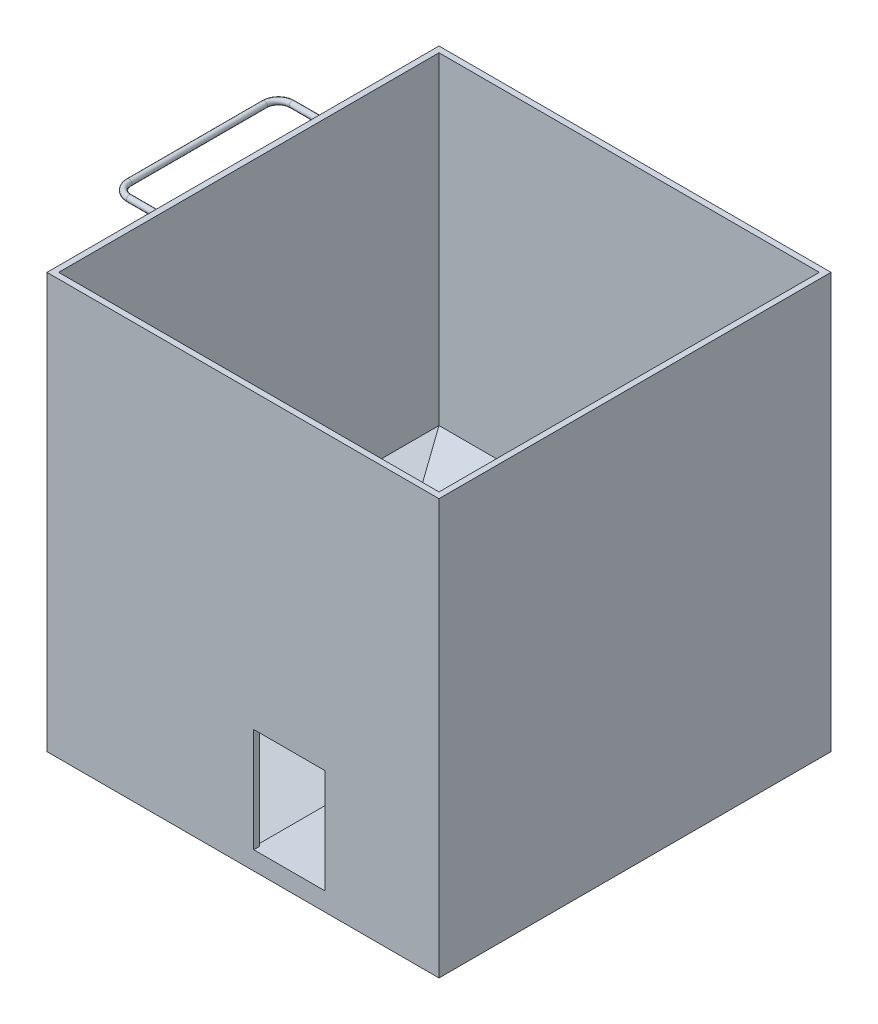
SolidWorks part; units mm, degrees
ref_plane "Front" through (0, 0, 0) normal (0, 0, 1) x (1, 0, 0)
ref_plane "Top" through (0, 0, 0) normal (0, 1, 0) x (1, 0, 0)
ref_plane "Right" through (0, 0, 0) normal (1, 0, 0) x (0, 0, -1)
sketch "Croquis1" plane through (0, 0, 0) normal (0, 1, 0) x (1, 0, 0)
  line L1 (0, 0) -> (850, 0)
  line L2 (0, 0) -> (0, 850)
  line L3 (0, 850) -> (850, 850)
  line L4 (850, 0) -> (850, 850)
  dimension "D1" = 850
  dimension "D2" = 850
extrude "Saliente-Extruir1" add sketch "Croquis1" along normal blind 700
shell "Vaciado1" thickness 12.7
sketch "Croquis2" plane through (0, 0, 0) normal (0, -1, 0) x (1, 0, 0)
  line L1 (0, -850) -> (850, -850)
  line L2 (0, -850) -> (0, 0)
  line L3 (0, 0) -> (850, 0)
  line L4 (850, -850) -> (850, 0)
extrude "Saliente-Extruir2" add sketch "Croquis2" along normal blind 200
sketch "Croquis3" plane through (0, -200, 0) normal (0, -1, 0) x (1, 0, 0)
  line L0 (425, 0) -> (425, -850) construction
  line L1 (850, 0) -> (0, 0) construction
  line L2 (0, -850) -> (850, -850) construction
  line L3 (0, -425) -> (850, -425) construction
  line L4 (0, 0) -> (0, -850) construction
  line L5 (850, -850) -> (850, 0) construction
  line L6 (229.4049, -55.6114) -> (229.4049, -105.6114)
  line L7 (770.5951, -55.6114) -> (620.5951, -55.6114)
  line L8 (770.5951, -55.6114) -> (770.5951, -105.6114)
  line L9 (770.5951, -105.6114) -> (620.5951, -105.6114)
  line L10 (620.5951, -55.6114) -> (620.5951, -105.6114)
  line L11 (79.4049, -105.6114) -> (229.4049, -105.6114)
  line L12 (79.4049, -55.6114) -> (79.4049, -105.6114)
  line L13 (79.4049, -55.6114) -> (229.4049, -55.6114)
  line L14 (79.4049, -794.3886) -> (229.4049, -794.3886)
  line L15 (79.4049, -794.3886) -> (79.4049, -744.3886)
  line L16 (79.4049, -744.3886) -> (229.4049, -744.3886)
  line L17 (620.5951, -794.3886) -> (620.5951, -744.3886)
  line L18 (770.5951, -744.3886) -> (620.5951, -744.3886)
  line L19 (770.5951, -794.3886) -> (770.5951, -744.3886)
  line L20 (770.5951, -794.3886) -> (620.5951, -794.3886)
  line L21 (229.4049, -794.3886) -> (229.4049, -744.3886)
  dimension "D1" = 150
  dimension "D2" = 50
extrude "Cortar-Extruir1" cut sketch "Croquis3" against normal blind 90
ref_plane "Plano1" through (0, 680, 0) normal (0, 1, 0) x (1, 0, 0)
ref_plane "Plano2" through (0, -160, 0) normal (0, -1, 0) x (-1, 0, 0)
sketch "Croquis6" plane through (0, -160, 0) normal (0, -1, 0) x (-1, 0, 0)
  line L5 (-12.7, 12.7) -> (-837.3, 12.7) construction
  line L6 (-602.7651, 12.7) -> (-442.7651, 12.7)
  line L7 (-602.7651, 12.7) -> (-602.7651, 172.7)
  line L8 (-602.7651, 172.7) -> (-442.7651, 172.7)
  line L9 (-442.7651, 12.7) -> (-442.7651, 172.7)
  dimension "D1" = 160
  dimension "D2" = 160
sketch "Croquis8" plane through (0, 0, 0) normal (0, 1, 0) x (1, 0, 0)
  line L1 (12.7, 12.7) -> (837.3, 12.7)
  line L2 (12.7, 12.7) -> (12.7, 837.3)
  line L3 (12.7, 837.3) -> (837.3, 837.3)
  line L4 (837.3, 12.7) -> (837.3, 837.3)
loft "Cortar-Recubrir1" cut profiles "Croquis8", "Croquis6"
sketch "Croquis9" plane through (837.3, 0, 0) normal (-1, 0, 0) x (0, 0, 1)
  line L6 (-507.3763, -153.7031) -> (-714.233, -153.7031)
  line L7 (-507.3763, -153.7031) -> (-507.3763, -56.1761)
  line L8 (-507.3763, -56.1761) -> (-714.233, -56.1761)
  line L9 (-714.233, -153.7031) -> (-714.233, -56.1761)
sketch "Croquis10" plane through (0, 0, 0) normal (-1, 0, 0) x (0, 0, 1)
  line L0 (-425, -200) -> (-425, 700) construction
  line L1 (0, -200) -> (-850, -200) construction
  line L2 (-850, 700) -> (0, 700) construction
  circle A0 centre (-248.2987, 680) radius 12.7
  circle A1 centre (-601.7013, 680) radius 12.7
  point P10 (-308.1908, 602.2675)
  dimension "D1" = 25.4
  dimension "D2" = 20
sketch "Croquis11" plane through (0, 680, 0) normal (0, 1, 0) x (1, 0, 0)
  line L1 (0, 248.2987) -> (-70, 248.2987)
  line L3 (0, 601.7013) -> (-70, 601.7013)
  line L4 (-100, 278.2987) -> (-100, 571.7013)
  arc A0 (-100, 571.7013) -> (-70, 601.7013) centre (-70, 571.7013) cw
  arc A1 (-100, 278.2987) -> (-70, 248.2987) centre (-70, 278.2987) ccw
  point P9 (-100, 248.2987)
  dimension "D2" = 30
  dimension "D1" = 100
sweep "Barrer4" add path "Croquis11" circular profile diameter 12.7 parameters "D3"=12.7
sketch "Croquis28" plane through (0, 0, -12.7) normal (0, 0, -1) x (-1, 0, 0)
  line L1 (-602.7651, -160) -> (-448.3432, -160)
  line L2 (-602.7651, -160) -> (-602.7651, 65.8054)
  line L3 (-602.7651, 65.8054) -> (-448.3432, 65.8054)
  line L4 (-448.3432, -160) -> (-448.3432, 65.8054)
extrude "Cortar-Extruir2" cut sketch "Croquis28" against normal up to next
